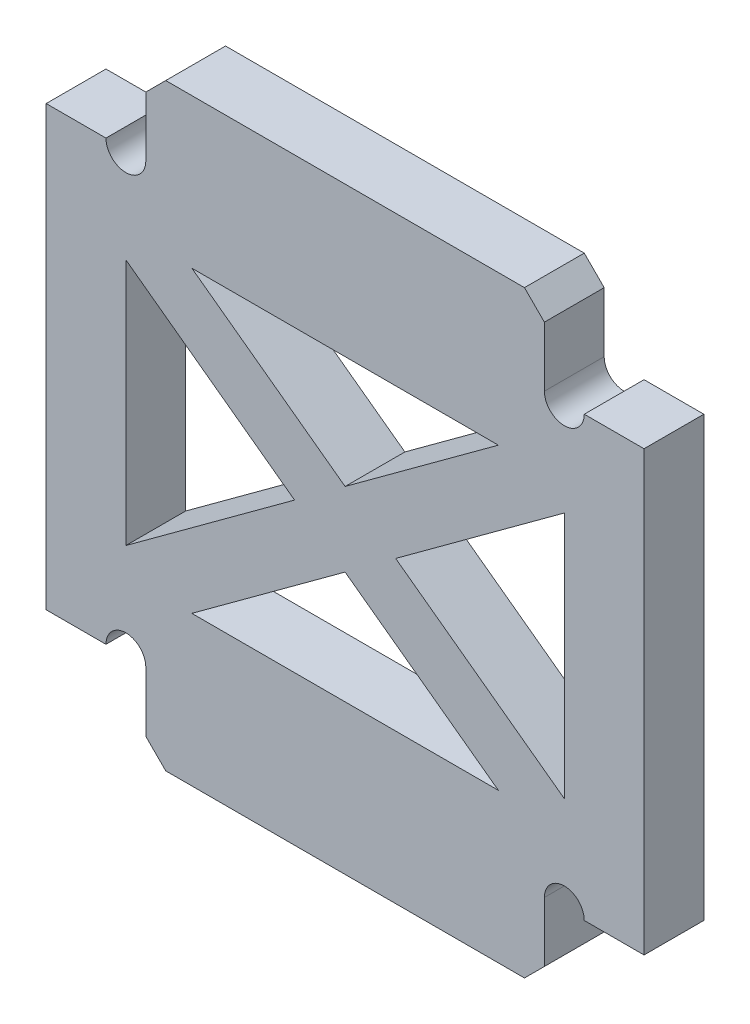
SolidWorks part; units mm, degrees
material "碳板"
ref_plane "前视基准面" through (0, 0, 0) normal (0, 0, 1) x (1, 0, 0)
ref_plane "上视基准面" through (0, 0, 0) normal (0, 1, 0) x (1, 0, 0)
ref_plane "右视基准面" through (0, 0, 0) normal (1, 0, 0) x (0, 0, -1)
sketch "草图1" plane through (0, 0, 0) normal (0, 0, 1) x (1, 0, 0)
  line L0 (0, 19.9183) -> (0, -17.9901) construction
  line L1 (-15, 11) -> (15, 11)
  line L2 (-15, 11) -> (-15, -11)
  line L3 (-15, -11) -> (15, -11)
  line L4 (15, 11) -> (15, -11)
  line L5 (-15, 11) -> (15, -11) construction
  line L6 (-15, -11) -> (15, 11) construction
  line L7 (-22.5399, 0) -> (24.3637, 0) construction
  line L8 (-10, 11) -> (-10, 15)
  line L9 (-10, 15) -> (10, 15)
  line L10 (10, 11) -> (10, 15)
  line L11 (10, -11) -> (10, -15)
  line L12 (-10, -15) -> (10, -15)
  line L13 (-10, -11) -> (-10, -15)
  line L14 (7.6908, 7.5) -> (-7.6908, 7.5)
  line L15 (-7.6908, 7.5) -> (0, 1.8601)
  line L16 (-2.5365, 0) -> (-11, 6.2066)
  line L17 (-11, 6.2066) -> (-11, -6.2066)
  line L18 (7.6908, 7.5) -> (0, 1.8601)
  line L19 (2.5365, 0) -> (11, 6.2066)
  line L20 (11, 6.2066) -> (11, -6.2066)
  line L21 (2.5365, 0) -> (11, -6.2066)
  line L22 (7.6908, -7.5) -> (-7.6908, -7.5)
  line L23 (-7.6908, -7.5) -> (0, -1.8601)
  line L24 (7.6908, -7.5) -> (0, -1.8601)
  line L25 (-2.5365, 0) -> (-11, -6.2066)
  circle A0 centre (-11, 11) radius 1
  circle A1 centre (11, 11) radius 1
  circle A2 centre (11, -11) radius 1
  circle A3 centre (-11, -11) radius 1
  point P0 (0, 0)
  point P15 (0, 15)
  point P34 (0, 7.5)
  point P38 (11, 0)
  point P42 (-11, 0)
  dimension "D4" = 2
  dimension "D1" = 30
  dimension "D2" = 4
  dimension "D3" = 20
  dimension "D5" = 4
  dimension "D6" = 1.5
  dimension "D7" = 1.5
  dimension "D8" = 4
  dimension "D9" = 3.5
extrude "凸台-拉伸1" add sketch "草图1" along normal mid plane 3 contours L3 A3 A2 L4 L1 A1 A0 L2 L24 L22 L23 L21 L19 L20 L14 L18 L15 L16 L25 L17 | L1 L10 L9 L8 | L3 L13 L12 L11
chamfer "倒角1" distance 1 angle 45 4 edges at (10, -15, 0) (-10, -15, 0) (10, 15, 0) (-10, 15, 0)
